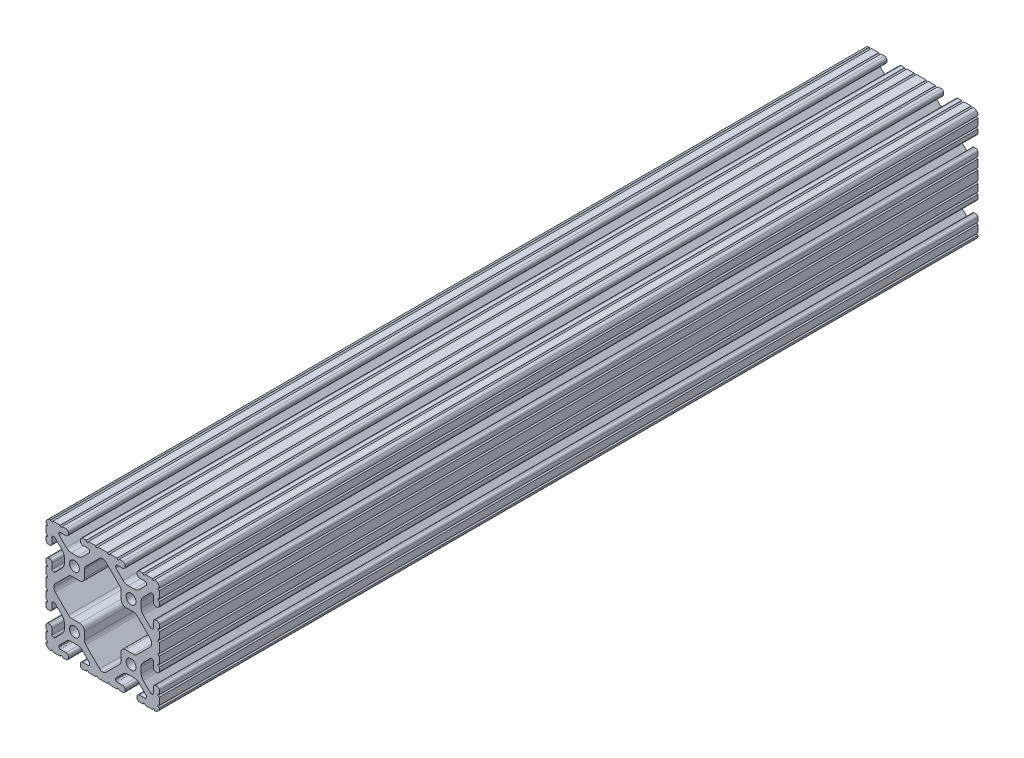
SolidWorks part; units mm, degrees
ref_plane "Front Plane" through (0, 0, 0) normal (0, 0, 1) x (1, 0, 0)
ref_plane "Top Plane" through (0, 0, 0) normal (0, 1, 0) x (1, 0, 0)
ref_plane "Right Plane" through (0, 0, 0) normal (1, 0, 0) x (0, 0, -1)
sketch "Sketch1" plane through (0, 0, 0) normal (0, 0, 1) x (1, 0, 0)
  line L0 (0, 38.1) -> (0, -38.1) construction
  line L1 (-38.1, -38.1) -> (38.1, -38.1) construction
  line L2 (-38.1, -38.1) -> (-38.1, 38.1) construction
  line L3 (-38.1, 38.1) -> (38.1, 38.1) construction
  line L4 (38.1, -38.1) -> (38.1, 38.1) construction
  line L5 (0, 38.1) -> (0, -38.1) construction
  line L6 (-38.1, 0) -> (38.1, 0) construction
  line L7 (-19.05, 19.05) -> (19.05, 19.05) construction
  line L8 (-19.05, 19.05) -> (-19.05, -19.05) construction
  line L9 (-19.05, -19.05) -> (19.05, -19.05) construction
  line L10 (19.05, 19.05) -> (19.05, -19.05) construction
  line L11 (-23.114, 38.1) -> (-23.114, -38.1) construction
  line L12 (-23.114, -38.1) -> (-14.986, 38.1) construction
  line L13 (-14.986, 38.1) -> (-14.986, -38.1) construction
  circle A0 centre (19.05, 19.05) radius 3.3274
  point P0 (0, 0)
  point P9 (0, 0)
  point P12 (-19.05, 0)
  line B0 (-11.3637, -22.8433) -> (-2.0515, -32.1555)
  line B1 (-12.2936, -15.4686) -> (-12.2936, -20.5983)
  line B2 (-20.769, -12.2936) -> (-15.4686, -12.2936)
  line B3 (-31.9021, -2.4756) -> (-23.0141, -11.3637)
  line B4 (-23.0141, 11.3637) -> (-31.9021, 2.4756)
  line B5 (-15.4686, 12.2936) -> (-20.769, 12.2936)
  line B6 (-12.2936, 20.5983) -> (-12.2936, 15.4686)
  line B7 (-2.0515, 32.1555) -> (-11.3637, 22.8433)
  line B8 (11.3637, 22.8433) -> (2.0515, 32.1555)
  line B9 (12.2936, 15.4686) -> (12.2936, 20.5983)
  line B10 (20.769, 12.2936) -> (15.4686, 12.2936)
  line B11 (31.9021, 2.4756) -> (23.0141, 11.3637)
  line B12 (23.0141, -11.3637) -> (31.9021, -2.4756)
  line B13 (15.4686, -12.2936) -> (20.769, -12.2936)
  line B14 (12.2936, -20.5983) -> (12.2936, -15.4686)
  line B15 (2.0515, -32.1555) -> (11.3637, -22.8433)
  line B16 (-4.7773, 38.1) -> (-9.6053, 38.1)
  line B17 (-11.1289, 38.1) -> (-13.4112, 38.1)
  line B18 (-14.986, 36.5252) -> (-14.986, 35.6108)
  line B19 (-13.4112, 34.036) -> (-9.652, 34.036)
  line B20 (-8.763, 33.147) -> (-8.763, 32.4935)
  line B21 (-9.0234, 31.8649) -> (-13.6907, 27.1976)
  line B22 (-17.0493, 25.8064) -> (-21.0507, 25.8064)
  line B23 (-24.4093, 27.1976) -> (-29.1002, 31.8885)
  line B24 (-29.337, 32.7207) -> (-29.337, 33.147)
  line B25 (-28.448, 34.036) -> (-24.6888, 34.036)
  line B26 (-23.114, 35.6108) -> (-23.114, 36.5252)
  line B27 (-24.6888, 38.1) -> (-27.0772, 38.1)
  line B28 (-28.6011, 38.1) -> (-33.4288, 38.1)
  line B29 (-38.1, 33.373) -> (-38.1, 28.5453)
  line B30 (-38.1, 27.0238) -> (-38.1, 24.6302)
  line B31 (-36.5252, 23.0554) -> (-35.6108, 23.0554)
  line B32 (-34.036, 24.6302) -> (-34.036, 28.448)
  line B33 (-33.147, 29.337) -> (-32.6643, 29.337)
  line B34 (-32.0357, 29.0766) -> (-27.1976, 24.2385)
  line B35 (-25.8064, 20.8799) -> (-25.8064, 17.2201)
  line B36 (-27.1976, 13.8615) -> (-31.9489, 9.1101)
  line B37 (-32.7869, 8.763) -> (-33.0603, 8.763)
  line B38 (-34.036, 9.7387) -> (-34.036, 13.4698)
  line B39 (-35.6108, 15.0446) -> (-36.5252, 15.0446)
  line B40 (-38.1, 13.4698) -> (-38.1, 11.075)
  line B41 (-38.1, 9.552) -> (-38.1, 4.7238)
  line B42 (-38.1, 3.2007) -> (-38.1, -3.2007)
  line B43 (-38.1, -4.7238) -> (-38.1, -9.552)
  line B44 (-38.1, -11.075) -> (-38.1, -13.4698)
  line B45 (-36.5252, -15.0446) -> (-35.6108, -15.0446)
  line B46 (-34.036, -13.4698) -> (-34.036, -9.7387)
  line B47 (-33.0603, -8.763) -> (-32.7869, -8.763)
  line B48 (-31.9489, -9.1101) -> (-27.1976, -13.8615)
  line B49 (-25.8064, -17.2201) -> (-25.8064, -20.8799)
  line B50 (-27.1976, -24.2385) -> (-32.0357, -29.0766)
  line B51 (-32.6643, -29.337) -> (-33.147, -29.337)
  line B52 (-34.036, -28.448) -> (-34.036, -24.6302)
  line B53 (-35.6108, -23.0554) -> (-36.5252, -23.0554)
  line B54 (-38.1, -24.6302) -> (-38.1, -27.0238)
  line B55 (-38.1, -28.5453) -> (-38.1, -33.373)
  line B56 (-33.4288, -38.1) -> (-28.6011, -38.1)
  line B57 (-27.0772, -38.1) -> (-24.6888, -38.1)
  line B58 (-23.114, -36.5252) -> (-23.114, -35.6108)
  line B59 (-24.6888, -34.036) -> (-28.448, -34.036)
  line B60 (-29.337, -33.147) -> (-29.337, -32.7207)
  line B61 (-29.1002, -31.8885) -> (-24.4093, -27.1976)
  line B62 (-21.0507, -25.8064) -> (-17.0493, -25.8064)
  line B63 (-13.6907, -27.1976) -> (-9.0234, -31.8649)
  line B64 (-8.763, -32.4935) -> (-8.763, -33.147)
  line B65 (-9.652, -34.036) -> (-13.4112, -34.036)
  line B66 (-14.986, -35.6108) -> (-14.986, -36.5252)
  line B67 (-13.4112, -38.1) -> (-11.1289, -38.1)
  line B68 (-9.6053, -38.1) -> (-4.7773, -38.1)
  line B69 (-3.2537, -38.1) -> (3.2537, -38.1)
  line B70 (4.7773, -38.1) -> (9.6053, -38.1)
  line B71 (11.1289, -38.1) -> (13.4112, -38.1)
  line B72 (14.986, -36.5252) -> (14.986, -35.6108)
  line B73 (13.4112, -34.036) -> (9.652, -34.036)
  line B74 (8.763, -33.147) -> (8.763, -32.4935)
  line B75 (9.0234, -31.8649) -> (13.6907, -27.1976)
  line B76 (17.0493, -25.8064) -> (21.0507, -25.8064)
  line B77 (24.4093, -27.1976) -> (29.1002, -31.8885)
  line B78 (29.337, -32.7207) -> (29.337, -33.147)
  line B79 (28.448, -34.036) -> (24.6888, -34.036)
  line B80 (23.114, -35.6108) -> (23.114, -36.5252)
  line B81 (24.6888, -38.1) -> (27.0772, -38.1)
  line B82 (28.6011, -38.1) -> (33.4288, -38.1)
  line B83 (38.1, -33.373) -> (38.1, -28.5453)
  line B84 (38.1, -27.0238) -> (38.1, -24.6302)
  line B85 (36.5252, -23.0554) -> (35.6108, -23.0554)
  line B86 (34.036, -24.6302) -> (34.036, -28.448)
  line B87 (33.147, -29.337) -> (32.6643, -29.337)
  line B88 (32.0357, -29.0766) -> (27.1976, -24.2385)
  line B89 (25.8064, -20.8799) -> (25.8064, -17.2201)
  line B90 (27.1976, -13.8615) -> (31.9489, -9.1101)
  line B91 (32.7869, -8.763) -> (33.0603, -8.763)
  line B92 (34.036, -9.7387) -> (34.036, -13.4698)
  line B93 (35.6108, -15.0446) -> (36.5252, -15.0446)
  line B94 (38.1, -13.4698) -> (38.1, -11.075)
  line B95 (38.1, -9.552) -> (38.1, -4.7238)
  line B96 (38.1, -3.2007) -> (38.1, 3.2007)
  line B97 (38.1, 4.7238) -> (38.1, 9.552)
  line B98 (38.1, 11.075) -> (38.1, 13.4698)
  line B99 (36.5252, 15.0446) -> (35.6108, 15.0446)
  line B100 (34.036, 13.4698) -> (34.036, 9.7387)
  line B101 (33.0603, 8.763) -> (32.7869, 8.763)
  line B102 (31.9489, 9.1101) -> (27.1976, 13.8615)
  line B103 (25.8064, 17.2201) -> (25.8064, 20.8799)
  line B104 (27.1976, 24.2385) -> (32.0357, 29.0766)
  line B105 (32.6643, 29.337) -> (33.147, 29.337)
  line B106 (34.036, 28.448) -> (34.036, 24.6302)
  line B107 (35.6108, 23.0554) -> (36.5252, 23.0554)
  line B108 (38.1, 24.6302) -> (38.1, 27.0238)
  line B109 (38.1, 28.5453) -> (38.1, 33.373)
  line B110 (33.4288, 38.1) -> (28.6011, 38.1)
  line B111 (27.0772, 38.1) -> (24.6888, 38.1)
  line B112 (23.114, 36.5252) -> (23.114, 35.6108)
  line B113 (24.6888, 34.036) -> (28.448, 34.036)
  line B114 (29.337, 33.147) -> (29.337, 32.7207)
  line B115 (29.1002, 31.8885) -> (24.4093, 27.1976)
  line B116 (21.0507, 25.8064) -> (17.0493, 25.8064)
  line B117 (13.6907, 27.1976) -> (9.0234, 31.8649)
  line B118 (8.763, 32.4935) -> (8.763, 33.147)
  line B119 (9.652, 34.036) -> (13.4112, 34.036)
  line B120 (14.986, 35.6108) -> (14.986, 36.5252)
  line B121 (13.4112, 38.1) -> (11.1289, 38.1)
  line B122 (9.6053, 38.1) -> (4.7773, 38.1)
  line B123 (3.2537, 38.1) -> (-3.2537, 38.1)
  circle B124 centre (-19.05, 19.05) radius 3.3274
  circle B125 centre (-19.05, -19.05) radius 3.3274
  circle B126 centre (19.05, -19.05) radius 3.3274
  circle B127 centre (19.05, 19.05) radius 3.3274
  arc B128 (0, -33.011) -> (2.0515, -32.1555) centre (-0.0139, -30.09) ccw
  arc B129 (-2.0515, -32.1555) -> (0, -33.011) centre (0.0139, -30.09) ccw
  arc B130 (-12.2936, -20.5983) -> (-11.3637, -22.8433) centre (-9.1186, -20.5983) ccw
  arc B131 (-12.2936, -15.4686) -> (-15.4686, -12.2936) centre (-15.4686, -15.4686) ccw
  arc B132 (-23.0141, -11.3637) -> (-20.769, -12.2936) centre (-20.769, -9.1186) ccw
  arc B133 (-32.7287, 0) -> (-31.9021, -2.4756) centre (-29.8367, -0.4102) ccw
  arc B134 (-31.9021, 2.4756) -> (-32.7287, 0) centre (-29.8367, 0.4102) ccw
  arc B135 (-20.769, 12.2936) -> (-23.0141, 11.3637) centre (-20.769, 9.1186) ccw
  arc B136 (-15.4686, 12.2936) -> (-12.2936, 15.4686) centre (-15.4686, 15.4686) ccw
  arc B137 (-11.3637, 22.8433) -> (-12.2936, 20.5983) centre (-9.1186, 20.5983) ccw
  arc B138 (0, 33.011) -> (-2.0515, 32.1555) centre (0.0139, 30.09) ccw
  arc B139 (2.0515, 32.1555) -> (0, 33.011) centre (-0.0139, 30.09) ccw
  arc B140 (12.2936, 20.5983) -> (11.3637, 22.8433) centre (9.1186, 20.5983) ccw
  arc B141 (12.2936, 15.4686) -> (15.4686, 12.2936) centre (15.4686, 15.4686) ccw
  arc B142 (23.0141, 11.3637) -> (20.769, 12.2936) centre (20.769, 9.1186) ccw
  arc B143 (32.7287, 0) -> (31.9021, 2.4756) centre (29.8367, 0.4102) ccw
  arc B144 (31.9021, -2.4756) -> (32.7287, 0) centre (29.8367, -0.4102) ccw
  arc B145 (20.769, -12.2936) -> (23.0141, -11.3637) centre (20.769, -9.1186) ccw
  arc B146 (15.4686, -12.2936) -> (12.2936, -15.4686) centre (15.4686, -15.4686) ccw
  arc B147 (11.3637, -22.8433) -> (12.2936, -20.5983) centre (9.1186, -20.5983) ccw
  arc B148 (-4.7773, 38.1) -> (-3.2537, 38.1) centre (-4.0155, 38.0824) ccw
  arc B149 (-11.1289, 38.1) -> (-9.6053, 38.1) centre (-10.3671, 38.0824) ccw
  arc B150 (-13.4112, 38.1) -> (-14.986, 36.5252) centre (-13.4112, 36.5252) ccw
  arc B151 (-14.986, 35.6108) -> (-13.4112, 34.036) centre (-13.4112, 35.6108) ccw
  arc B152 (-8.763, 33.147) -> (-9.652, 34.036) centre (-9.652, 33.147) ccw
  arc B153 (-9.0234, 31.8649) -> (-8.763, 32.4935) centre (-9.652, 32.4935) ccw
  arc B154 (-17.0493, 25.8064) -> (-13.6907, 27.1976) centre (-17.0493, 30.5562) ccw
  arc B155 (-24.4093, 27.1976) -> (-21.0507, 25.8064) centre (-21.0507, 30.5562) ccw
  arc B156 (-29.337, 32.7207) -> (-29.1002, 31.8885) centre (-28.4716, 32.5172) ccw
  arc B157 (-28.448, 34.036) -> (-29.337, 33.147) centre (-28.448, 33.147) ccw
  arc B158 (-24.6888, 34.036) -> (-23.114, 35.6108) centre (-24.6888, 35.6108) ccw
  arc B159 (-23.114, 36.5252) -> (-24.6888, 38.1) centre (-24.6888, 36.5252) ccw
  arc B160 (-28.6011, 38.1) -> (-27.0772, 38.1) centre (-27.8392, 38.0824) ccw
  arc B161 (-34.9527, 38.1) -> (-33.4288, 38.1) centre (-34.1907, 38.0824) ccw
  arc B162 (-34.9527, 38.1) -> (-37.0861, 37.1826) centre (-34.8521, 34.9266) ccw
  arc B163 (-37.0861, 37.1826) -> (-38.1, 34.8455) centre (-34.925, 34.8566) ccw
  arc B164 (-38.1, 33.373) -> (-38.1, 34.8455) centre (-37.9035, 34.1092) ccw
  arc B165 (-38.1, 27.0238) -> (-38.1, 28.5453) centre (-37.9035, 27.7845) ccw
  arc B166 (-38.1, 24.6302) -> (-36.5252, 23.0554) centre (-36.5252, 24.6302) ccw
  arc B167 (-35.6108, 23.0554) -> (-34.036, 24.6302) centre (-35.6108, 24.6302) ccw
  arc B168 (-33.147, 29.337) -> (-34.036, 28.448) centre (-33.147, 28.448) ccw
  arc B169 (-32.0357, 29.0766) -> (-32.6643, 29.337) centre (-32.6643, 28.448) ccw
  arc B170 (-25.8064, 20.8799) -> (-27.1976, 24.2385) centre (-30.5562, 20.8799) ccw
  arc B171 (-27.1976, 13.8615) -> (-25.8064, 17.2201) centre (-30.5562, 17.2201) ccw
  arc B172 (-32.7869, 8.763) -> (-31.9489, 9.1101) centre (-32.7869, 9.9481) ccw
  arc B173 (-34.036, 9.7387) -> (-33.0603, 8.763) centre (-33.0603, 9.7387) ccw
  arc B174 (-34.036, 13.4698) -> (-35.6108, 15.0446) centre (-35.6108, 13.4698) ccw
  arc B175 (-36.5252, 15.0446) -> (-38.1, 13.4698) centre (-36.5252, 13.4698) ccw
  arc B176 (-38.1, 9.552) -> (-38.1, 11.075) centre (-37.9035, 10.3135) ccw
  arc B177 (-38.1, 3.2007) -> (-38.1, 4.7238) centre (-37.9035, 3.9622) ccw
  arc B178 (-38.1, -4.7238) -> (-38.1, -3.2007) centre (-37.9035, -3.9622) ccw
  arc B179 (-38.1, -11.075) -> (-38.1, -9.552) centre (-37.9035, -10.3135) ccw
  arc B180 (-38.1, -13.4698) -> (-36.5252, -15.0446) centre (-36.5252, -13.4698) ccw
  arc B181 (-35.6108, -15.0446) -> (-34.036, -13.4698) centre (-35.6108, -13.4698) ccw
  arc B182 (-33.0603, -8.763) -> (-34.036, -9.7387) centre (-33.0603, -9.7387) ccw
  arc B183 (-31.9489, -9.1101) -> (-32.7869, -8.763) centre (-32.7869, -9.9481) ccw
  arc B184 (-25.8064, -17.2201) -> (-27.1976, -13.8615) centre (-30.5562, -17.2201) ccw
  arc B185 (-27.1976, -24.2385) -> (-25.8064, -20.8799) centre (-30.5562, -20.8799) ccw
  arc B186 (-32.6643, -29.337) -> (-32.0357, -29.0766) centre (-32.6643, -28.448) ccw
  arc B187 (-34.036, -28.448) -> (-33.147, -29.337) centre (-33.147, -28.448) ccw
  arc B188 (-34.036, -24.6302) -> (-35.6108, -23.0554) centre (-35.6108, -24.6302) ccw
  arc B189 (-36.5252, -23.0554) -> (-38.1, -24.6302) centre (-36.5252, -24.6302) ccw
  arc B190 (-38.1, -28.5453) -> (-38.1, -27.0238) centre (-37.9035, -27.7845) ccw
  arc B191 (-38.1, -34.8455) -> (-38.1, -33.373) centre (-37.9035, -34.1092) ccw
  arc B192 (-38.1, -34.8455) -> (-37.0861, -37.1826) centre (-34.925, -34.8566) ccw
  arc B193 (-37.0861, -37.1826) -> (-34.9527, -38.1) centre (-34.8521, -34.9266) ccw
  arc B194 (-33.4288, -38.1) -> (-34.9527, -38.1) centre (-34.1907, -38.0824) ccw
  arc B195 (-27.0772, -38.1) -> (-28.6011, -38.1) centre (-27.8392, -38.0824) ccw
  arc B196 (-24.6888, -38.1) -> (-23.114, -36.5252) centre (-24.6888, -36.5252) ccw
  arc B197 (-23.114, -35.6108) -> (-24.6888, -34.036) centre (-24.6888, -35.6108) ccw
  arc B198 (-29.337, -33.147) -> (-28.448, -34.036) centre (-28.448, -33.147) ccw
  arc B199 (-29.1002, -31.8885) -> (-29.337, -32.7207) centre (-28.4716, -32.5172) ccw
  arc B200 (-21.0507, -25.8064) -> (-24.4093, -27.1976) centre (-21.0507, -30.5562) ccw
  arc B201 (-13.6907, -27.1976) -> (-17.0493, -25.8064) centre (-17.0493, -30.5562) ccw
  arc B202 (-8.763, -32.4935) -> (-9.0234, -31.8649) centre (-9.652, -32.4935) ccw
  arc B203 (-9.652, -34.036) -> (-8.763, -33.147) centre (-9.652, -33.147) ccw
  arc B204 (-13.4112, -34.036) -> (-14.986, -35.6108) centre (-13.4112, -35.6108) ccw
  arc B205 (-14.986, -36.5252) -> (-13.4112, -38.1) centre (-13.4112, -36.5252) ccw
  arc B206 (-9.6053, -38.1) -> (-11.1289, -38.1) centre (-10.3671, -38.0824) ccw
  arc B207 (-3.2537, -38.1) -> (-4.7773, -38.1) centre (-4.0155, -38.0824) ccw
  arc B208 (4.7773, -38.1) -> (3.2537, -38.1) centre (4.0155, -38.0824) ccw
  arc B209 (11.1289, -38.1) -> (9.6053, -38.1) centre (10.3671, -38.0824) ccw
  arc B210 (13.4112, -38.1) -> (14.986, -36.5252) centre (13.4112, -36.5252) ccw
  arc B211 (14.986, -35.6108) -> (13.4112, -34.036) centre (13.4112, -35.6108) ccw
  arc B212 (8.763, -33.147) -> (9.652, -34.036) centre (9.652, -33.147) ccw
  arc B213 (9.0234, -31.8649) -> (8.763, -32.4935) centre (9.652, -32.4935) ccw
  arc B214 (17.0493, -25.8064) -> (13.6907, -27.1976) centre (17.0493, -30.5562) ccw
  arc B215 (24.4093, -27.1976) -> (21.0507, -25.8064) centre (21.0507, -30.5562) ccw
  arc B216 (29.337, -32.7207) -> (29.1002, -31.8885) centre (28.4716, -32.5172) ccw
  arc B217 (28.448, -34.036) -> (29.337, -33.147) centre (28.448, -33.147) ccw
  arc B218 (24.6888, -34.036) -> (23.114, -35.6108) centre (24.6888, -35.6108) ccw
  arc B219 (23.114, -36.5252) -> (24.6888, -38.1) centre (24.6888, -36.5252) ccw
  arc B220 (28.6011, -38.1) -> (27.0772, -38.1) centre (27.8392, -38.0824) ccw
  arc B221 (34.9527, -38.1) -> (33.4288, -38.1) centre (34.1907, -38.0824) ccw
  arc B222 (34.9527, -38.1) -> (37.0861, -37.1826) centre (34.8521, -34.9266) ccw
  arc B223 (37.0861, -37.1826) -> (38.1, -34.8455) centre (34.925, -34.8566) ccw
  arc B224 (38.1, -33.373) -> (38.1, -34.8455) centre (37.9035, -34.1092) ccw
  arc B225 (38.1, -27.0238) -> (38.1, -28.5453) centre (37.9035, -27.7845) ccw
  arc B226 (38.1, -24.6302) -> (36.5252, -23.0554) centre (36.5252, -24.6302) ccw
  arc B227 (35.6108, -23.0554) -> (34.036, -24.6302) centre (35.6108, -24.6302) ccw
  arc B228 (33.147, -29.337) -> (34.036, -28.448) centre (33.147, -28.448) ccw
  arc B229 (32.0357, -29.0766) -> (32.6643, -29.337) centre (32.6643, -28.448) ccw
  arc B230 (25.8064, -20.8799) -> (27.1976, -24.2385) centre (30.5562, -20.8799) ccw
  arc B231 (27.1976, -13.8615) -> (25.8064, -17.2201) centre (30.5562, -17.2201) ccw
  arc B232 (32.7869, -8.763) -> (31.9489, -9.1101) centre (32.7869, -9.9481) ccw
  arc B233 (34.036, -9.7387) -> (33.0603, -8.763) centre (33.0603, -9.7387) ccw
  arc B234 (34.036, -13.4698) -> (35.6108, -15.0446) centre (35.6108, -13.4698) ccw
  arc B235 (36.5252, -15.0446) -> (38.1, -13.4698) centre (36.5252, -13.4698) ccw
  arc B236 (38.1, -9.552) -> (38.1, -11.075) centre (37.9035, -10.3135) ccw
  arc B237 (38.1, -3.2007) -> (38.1, -4.7238) centre (37.9035, -3.9622) ccw
  arc B238 (38.1, 4.7238) -> (38.1, 3.2007) centre (37.9035, 3.9622) ccw
  arc B239 (38.1, 11.075) -> (38.1, 9.552) centre (37.9035, 10.3135) ccw
  arc B240 (38.1, 13.4698) -> (36.5252, 15.0446) centre (36.5252, 13.4698) ccw
  arc B241 (35.6108, 15.0446) -> (34.036, 13.4698) centre (35.6108, 13.4698) ccw
  arc B242 (33.0603, 8.763) -> (34.036, 9.7387) centre (33.0603, 9.7387) ccw
  arc B243 (31.9489, 9.1101) -> (32.7869, 8.763) centre (32.7869, 9.9481) ccw
  arc B244 (25.8064, 17.2201) -> (27.1976, 13.8615) centre (30.5562, 17.2201) ccw
  arc B245 (27.1976, 24.2385) -> (25.8064, 20.8799) centre (30.5562, 20.8799) ccw
  arc B246 (32.6643, 29.337) -> (32.0357, 29.0766) centre (32.6643, 28.448) ccw
  arc B247 (34.036, 28.448) -> (33.147, 29.337) centre (33.147, 28.448) ccw
  arc B248 (34.036, 24.6302) -> (35.6108, 23.0554) centre (35.6108, 24.6302) ccw
  arc B249 (36.5252, 23.0554) -> (38.1, 24.6302) centre (36.5252, 24.6302) ccw
  arc B250 (38.1, 28.5453) -> (38.1, 27.0238) centre (37.9035, 27.7845) ccw
  arc B251 (38.1, 34.8455) -> (38.1, 33.373) centre (37.9035, 34.1092) ccw
  arc B252 (38.1, 34.8455) -> (37.0861, 37.1826) centre (34.925, 34.8566) ccw
  arc B253 (37.0861, 37.1826) -> (34.9527, 38.1) centre (34.8521, 34.9266) ccw
  arc B254 (33.4288, 38.1) -> (34.9527, 38.1) centre (34.1907, 38.0824) ccw
  arc B255 (27.0772, 38.1) -> (28.6011, 38.1) centre (27.8392, 38.0824) ccw
  arc B256 (24.6888, 38.1) -> (23.114, 36.5252) centre (24.6888, 36.5252) ccw
  arc B257 (23.114, 35.6108) -> (24.6888, 34.036) centre (24.6888, 35.6108) ccw
  arc B258 (29.337, 33.147) -> (28.448, 34.036) centre (28.448, 33.147) ccw
  arc B259 (29.1002, 31.8885) -> (29.337, 32.7207) centre (28.4716, 32.5172) ccw
  arc B260 (21.0507, 25.8064) -> (24.4093, 27.1976) centre (21.0507, 30.5562) ccw
  arc B261 (13.6907, 27.1976) -> (17.0493, 25.8064) centre (17.0493, 30.5562) ccw
  arc B262 (8.763, 32.4935) -> (9.0234, 31.8649) centre (9.652, 32.4935) ccw
  arc B263 (9.652, 34.036) -> (8.763, 33.147) centre (9.652, 33.147) ccw
  arc B264 (13.4112, 34.036) -> (14.986, 35.6108) centre (13.4112, 35.6108) ccw
  arc B265 (14.986, 36.5252) -> (13.4112, 38.1) centre (13.4112, 36.5252) ccw
  arc B266 (9.6053, 38.1) -> (11.1289, 38.1) centre (10.3671, 38.0824) ccw
  arc B267 (3.2537, 38.1) -> (4.7773, 38.1) centre (4.0155, 38.0824) ccw
  dimension "Center Hole Diameter" = 6.6548
  dimension "Rail Width" = 76.2
  dimension "Rail Height" = 76.2
  dimension "T-Slot Width" = 8.128
sketch_block_instance "Block1-1"
sketch_block "Block1"
sketch "Sketch2" plane through (0, 0, 0) normal (1, 0, 0) x (0, 0, -1)
  line L0 (-275, 0) -> (275, 0) construction
  line L1 (-275, 38.1) -> (-275, -38.1) construction
  line L2 (-275, -38.1) -> (275, -38.1) construction
  line L3 (275, -38.1) -> (275, 38.1) construction
  line L4 (-173.4, 0) -> (-173.4, 38.1) construction
  line L5 (-173.4, 38.1) -> (173.4, 38.1) construction
  line L6 (173.4, 38.1) -> (173.4, 0) construction
  point P5 (173.4, 0)
  point P10 (-173.4, 0)
  dimension "D1" = 101.6
  dimension "Length" = 550
  dimension "D2" = 101.6
sketch "Sketch3" plane through (0, 0, 0) normal (0, 0, 1) x (1, 0, 0)
  line L0 (-11.3637, -22.8433) -> (-2.0515, -32.1555) construction
  line L1 (-12.2936, -15.4686) -> (-12.2936, -20.5983) construction
  line L2 (-20.769, -12.2936) -> (-15.4686, -12.2936) construction
  line L3 (-31.9021, -2.4756) -> (-23.0141, -11.3637) construction
  line L4 (-23.0141, 11.3637) -> (-31.9021, 2.4756) construction
  line L5 (-15.4686, 12.2936) -> (-20.769, 12.2936) construction
  line L6 (-12.2936, 20.5983) -> (-12.2936, 15.4686) construction
  line L7 (-2.0515, 32.1555) -> (-11.3637, 22.8433) construction
  line L8 (11.3637, 22.8433) -> (2.0515, 32.1555) construction
  line L9 (12.2936, 15.4686) -> (12.2936, 20.5983) construction
  line L10 (20.769, 12.2936) -> (15.4686, 12.2936) construction
  line L11 (31.9021, 2.4756) -> (23.0141, 11.3637) construction
  line L12 (23.0141, -11.3637) -> (31.9021, -2.4756) construction
  line L13 (15.4686, -12.2936) -> (20.769, -12.2936) construction
  line L14 (12.2936, -20.5983) -> (12.2936, -15.4686) construction
  line L15 (2.0515, -32.1555) -> (11.3637, -22.8433) construction
  line L16 (34.036, 28.448) -> (34.036, 24.6302) construction
  line L17 (35.6108, 23.0554) -> (36.5252, 23.0554) construction
  line L18 (38.1, 24.6302) -> (38.1, 27.0238) construction
  line L19 (38.1, 28.5453) -> (38.1, 33.373) construction
  line L20 (33.4288, 38.1) -> (28.6011, 38.1) construction
  line L21 (27.0772, 38.1) -> (24.6888, 38.1) construction
  line L22 (23.114, 36.5252) -> (23.114, 35.6108) construction
  line L23 (24.6888, 34.036) -> (28.448, 34.036) construction
  line L24 (29.337, 33.147) -> (29.337, 32.7207) construction
  line L25 (29.1002, 31.8885) -> (24.4093, 27.1976) construction
  line L26 (21.0507, 25.8064) -> (17.0493, 25.8064) construction
  line L27 (13.6907, 27.1976) -> (9.0234, 31.8649) construction
  line L28 (8.763, 32.4935) -> (8.763, 33.147) construction
  line L29 (9.652, 34.036) -> (13.4112, 34.036) construction
  line L30 (14.986, 35.6108) -> (14.986, 36.5252) construction
  line L31 (13.4112, 38.1) -> (11.1289, 38.1) construction
  line L32 (9.6053, 38.1) -> (4.7773, 38.1) construction
  line L33 (3.2537, 38.1) -> (-3.2537, 38.1) construction
  line L34 (-4.7773, 38.1) -> (-9.6053, 38.1) construction
  line L35 (-11.1289, 38.1) -> (-13.4112, 38.1) construction
  line L36 (-14.986, 36.5252) -> (-14.986, 35.6108) construction
  line L37 (-13.4112, 34.036) -> (-9.652, 34.036) construction
  line L38 (-8.763, 33.147) -> (-8.763, 32.4935) construction
  line L39 (-9.0234, 31.8649) -> (-13.6907, 27.1976) construction
  line L40 (-17.0493, 25.8064) -> (-21.0507, 25.8064) construction
  line L41 (-24.4093, 27.1976) -> (-29.1002, 31.8885) construction
  line L42 (-29.337, 32.7207) -> (-29.337, 33.147) construction
  line L43 (-28.448, 34.036) -> (-24.6888, 34.036) construction
  line L44 (-23.114, 35.6108) -> (-23.114, 36.5252) construction
  line L45 (-24.6888, 38.1) -> (-27.0772, 38.1) construction
  line L46 (-28.6011, 38.1) -> (-33.4288, 38.1) construction
  line L47 (-38.1, 33.373) -> (-38.1, 28.5453) construction
  line L48 (-38.1, 27.0238) -> (-38.1, 24.6302) construction
  line L49 (-36.5252, 23.0554) -> (-35.6108, 23.0554) construction
  line L50 (-34.036, 24.6302) -> (-34.036, 28.448) construction
  line L51 (-33.147, 29.337) -> (-32.6643, 29.337) construction
  line L52 (-32.0357, 29.0766) -> (-27.1976, 24.2385) construction
  line L53 (-25.8064, 20.8799) -> (-25.8064, 17.2201) construction
  line L54 (-27.1976, 13.8615) -> (-31.9489, 9.1101) construction
  line L55 (-32.7869, 8.763) -> (-33.0603, 8.763) construction
  line L56 (-34.036, 9.7387) -> (-34.036, 13.4698) construction
  line L57 (-35.6108, 15.0446) -> (-36.5252, 15.0446) construction
  line L58 (-38.1, 13.4698) -> (-38.1, 11.075) construction
  line L59 (-38.1, 9.552) -> (-38.1, 4.7238) construction
  line L60 (-38.1, 3.2007) -> (-38.1, -3.2007) construction
  line L61 (-38.1, -4.7238) -> (-38.1, -9.552) construction
  line L62 (-38.1, -11.075) -> (-38.1, -13.4698) construction
  line L63 (-36.5252, -15.0446) -> (-35.6108, -15.0446) construction
  line L64 (-34.036, -13.4698) -> (-34.036, -9.7387) construction
  line L65 (-33.0603, -8.763) -> (-32.7869, -8.763) construction
  line L66 (-31.9489, -9.1101) -> (-27.1976, -13.8615) construction
  line L67 (-25.8064, -17.2201) -> (-25.8064, -20.8799) construction
  line L68 (-27.1976, -24.2385) -> (-32.0357, -29.0766) construction
  line L69 (-32.6643, -29.337) -> (-33.147, -29.337) construction
  line L70 (-34.036, -28.448) -> (-34.036, -24.6302) construction
  line L71 (-35.6108, -23.0554) -> (-36.5252, -23.0554) construction
  line L72 (-38.1, -24.6302) -> (-38.1, -27.0238) construction
  line L73 (-38.1, -28.5453) -> (-38.1, -33.373) construction
  line L74 (-33.4288, -38.1) -> (-28.6011, -38.1) construction
  line L75 (-27.0772, -38.1) -> (-24.6888, -38.1) construction
  line L76 (-23.114, -36.5252) -> (-23.114, -35.6108) construction
  line L77 (-24.6888, -34.036) -> (-28.448, -34.036) construction
  line L78 (-29.337, -33.147) -> (-29.337, -32.7207) construction
  line L79 (-29.1002, -31.8885) -> (-24.4093, -27.1976) construction
  line L80 (-21.0507, -25.8064) -> (-17.0493, -25.8064) construction
  line L81 (-13.6907, -27.1976) -> (-9.0234, -31.8649) construction
  line L82 (-8.763, -32.4935) -> (-8.763, -33.147) construction
  line L83 (-9.652, -34.036) -> (-13.4112, -34.036) construction
  line L84 (-14.986, -35.6108) -> (-14.986, -36.5252) construction
  line L85 (-13.4112, -38.1) -> (-11.1289, -38.1) construction
  line L86 (-9.6053, -38.1) -> (-4.7773, -38.1) construction
  line L87 (-3.2537, -38.1) -> (3.2537, -38.1) construction
  line L88 (4.7773, -38.1) -> (9.6053, -38.1) construction
  line L89 (11.1289, -38.1) -> (13.4112, -38.1) construction
  line L90 (14.986, -36.5252) -> (14.986, -35.6108) construction
  line L91 (13.4112, -34.036) -> (9.652, -34.036) construction
  line L92 (8.763, -33.147) -> (8.763, -32.4935) construction
  line L93 (9.0234, -31.8649) -> (13.6907, -27.1976) construction
  line L94 (17.0493, -25.8064) -> (21.0507, -25.8064) construction
  line L95 (24.4093, -27.1976) -> (29.1002, -31.8885) construction
  line L96 (29.337, -32.7207) -> (29.337, -33.147) construction
  line L97 (28.448, -34.036) -> (24.6888, -34.036) construction
  line L98 (23.114, -35.6108) -> (23.114, -36.5252) construction
  line L99 (24.6888, -38.1) -> (27.0772, -38.1) construction
  line L100 (28.6011, -38.1) -> (33.4288, -38.1) construction
  line L101 (38.1, -33.373) -> (38.1, -28.5453) construction
  line L102 (38.1, -27.0238) -> (38.1, -24.6302) construction
  line L103 (36.5252, -23.0554) -> (35.6108, -23.0554) construction
  line L104 (34.036, -24.6302) -> (34.036, -28.448) construction
  line L105 (33.147, -29.337) -> (32.6643, -29.337) construction
  line L106 (32.0357, -29.0766) -> (27.1976, -24.2385) construction
  line L107 (25.8064, -20.8799) -> (25.8064, -17.2201) construction
  line L108 (27.1976, -13.8615) -> (31.9489, -9.1101) construction
  line L109 (32.7869, -8.763) -> (33.0603, -8.763) construction
  line L110 (34.036, -9.7387) -> (34.036, -13.4698) construction
  line L111 (35.6108, -15.0446) -> (36.5252, -15.0446) construction
  line L112 (38.1, -13.4698) -> (38.1, -11.075) construction
  line L113 (38.1, -9.552) -> (38.1, -4.7238) construction
  line L114 (38.1, -3.2007) -> (38.1, 3.2007) construction
  line L115 (38.1, 4.7238) -> (38.1, 9.552) construction
  line L116 (38.1, 11.075) -> (38.1, 13.4698) construction
  line L117 (36.5252, 15.0446) -> (35.6108, 15.0446) construction
  line L118 (34.036, 13.4698) -> (34.036, 9.7387) construction
  line L119 (33.0603, 8.763) -> (32.7869, 8.763) construction
  line L120 (31.9489, 9.1101) -> (27.1976, 13.8615) construction
  line L121 (25.8064, 17.2201) -> (25.8064, 20.8799) construction
  line L122 (27.1976, 24.2385) -> (32.0357, 29.0766) construction
  line L123 (32.6643, 29.337) -> (33.147, 29.337) construction
  line L124 (-11.3637, -22.8433) -> (-2.0515, -32.1555)
  line L125 (-12.2936, -15.4686) -> (-12.2936, -20.5983)
  line L126 (-20.769, -12.2936) -> (-15.4686, -12.2936)
  line L127 (-31.9021, -2.4756) -> (-23.0141, -11.3637)
  line L128 (-23.0141, 11.3637) -> (-31.9021, 2.4756)
  line L129 (-15.4686, 12.2936) -> (-20.769, 12.2936)
  line L130 (-12.2936, 20.5983) -> (-12.2936, 15.4686)
  line L131 (-2.0515, 32.1555) -> (-11.3637, 22.8433)
  line L132 (11.3637, 22.8433) -> (2.0515, 32.1555)
  line L133 (12.2936, 15.4686) -> (12.2936, 20.5983)
  line L134 (20.769, 12.2936) -> (15.4686, 12.2936)
  line L135 (31.9021, 2.4756) -> (23.0141, 11.3637)
  line L136 (23.0141, -11.3637) -> (31.9021, -2.4756)
  line L137 (15.4686, -12.2936) -> (20.769, -12.2936)
  line L138 (12.2936, -20.5983) -> (12.2936, -15.4686)
  line L139 (2.0515, -32.1555) -> (11.3637, -22.8433)
  line L140 (34.036, 28.448) -> (34.036, 24.6302)
  line L141 (35.6108, 23.0554) -> (36.5252, 23.0554)
  line L142 (38.1, 24.6302) -> (38.1, 27.0238)
  line L143 (38.1, 28.5453) -> (38.1, 33.373)
  line L144 (33.4288, 38.1) -> (28.6011, 38.1)
  line L145 (27.0772, 38.1) -> (24.6888, 38.1)
  line L146 (23.114, 36.5252) -> (23.114, 35.6108)
  line L147 (24.6888, 34.036) -> (28.448, 34.036)
  line L148 (29.337, 33.147) -> (29.337, 32.7207)
  line L149 (29.1002, 31.8885) -> (24.4093, 27.1976)
  line L150 (21.0507, 25.8064) -> (17.0493, 25.8064)
  line L151 (13.6907, 27.1976) -> (9.0234, 31.8649)
  line L152 (8.763, 32.4935) -> (8.763, 33.147)
  line L153 (9.652, 34.036) -> (13.4112, 34.036)
  line L154 (14.986, 35.6108) -> (14.986, 36.5252)
  line L155 (13.4112, 38.1) -> (11.1289, 38.1)
  line L156 (9.6053, 38.1) -> (4.7773, 38.1)
  line L157 (3.2537, 38.1) -> (-3.2537, 38.1)
  line L158 (-4.7773, 38.1) -> (-9.6053, 38.1)
  line L159 (-11.1289, 38.1) -> (-13.4112, 38.1)
  line L160 (-14.986, 36.5252) -> (-14.986, 35.6108)
  line L161 (-13.4112, 34.036) -> (-9.652, 34.036)
  line L162 (-8.763, 33.147) -> (-8.763, 32.4935)
  line L163 (-9.0234, 31.8649) -> (-13.6907, 27.1976)
  line L164 (-17.0493, 25.8064) -> (-21.0507, 25.8064)
  line L165 (-24.4093, 27.1976) -> (-29.1002, 31.8885)
  line L166 (-29.337, 32.7207) -> (-29.337, 33.147)
  line L167 (-28.448, 34.036) -> (-24.6888, 34.036)
  line L168 (-23.114, 35.6108) -> (-23.114, 36.5252)
  line L169 (-24.6888, 38.1) -> (-27.0772, 38.1)
  line L170 (-28.6011, 38.1) -> (-33.4288, 38.1)
  line L171 (-38.1, 33.373) -> (-38.1, 28.5453)
  line L172 (-38.1, 27.0238) -> (-38.1, 24.6302)
  line L173 (-36.5252, 23.0554) -> (-35.6108, 23.0554)
  line L174 (-34.036, 24.6302) -> (-34.036, 28.448)
  line L175 (-33.147, 29.337) -> (-32.6643, 29.337)
  line L176 (-32.0357, 29.0766) -> (-27.1976, 24.2385)
  line L177 (-25.8064, 20.8799) -> (-25.8064, 17.2201)
  line L178 (-27.1976, 13.8615) -> (-31.9489, 9.1101)
  line L179 (-32.7869, 8.763) -> (-33.0603, 8.763)
  line L180 (-34.036, 9.7387) -> (-34.036, 13.4698)
  line L181 (-35.6108, 15.0446) -> (-36.5252, 15.0446)
  line L182 (-38.1, 13.4698) -> (-38.1, 11.075)
  line L183 (-38.1, 9.552) -> (-38.1, 4.7238)
  line L184 (-38.1, 3.2007) -> (-38.1, -3.2007)
  line L185 (-38.1, -4.7238) -> (-38.1, -9.552)
  line L186 (-38.1, -11.075) -> (-38.1, -13.4698)
  line L187 (-36.5252, -15.0446) -> (-35.6108, -15.0446)
  line L188 (-34.036, -13.4698) -> (-34.036, -9.7387)
  line L189 (-33.0603, -8.763) -> (-32.7869, -8.763)
  line L190 (-31.9489, -9.1101) -> (-27.1976, -13.8615)
  line L191 (-25.8064, -17.2201) -> (-25.8064, -20.8799)
  line L192 (-27.1976, -24.2385) -> (-32.0357, -29.0766)
  line L193 (-32.6643, -29.337) -> (-33.147, -29.337)
  line L194 (-34.036, -28.448) -> (-34.036, -24.6302)
  line L195 (-35.6108, -23.0554) -> (-36.5252, -23.0554)
  line L196 (-38.1, -24.6302) -> (-38.1, -27.0238)
  line L197 (-38.1, -28.5453) -> (-38.1, -33.373)
  line L198 (-33.4288, -38.1) -> (-28.6011, -38.1)
  line L199 (-27.0772, -38.1) -> (-24.6888, -38.1)
  line L200 (-23.114, -36.5252) -> (-23.114, -35.6108)
  line L201 (-24.6888, -34.036) -> (-28.448, -34.036)
  line L202 (-29.337, -33.147) -> (-29.337, -32.7207)
  line L203 (-29.1002, -31.8885) -> (-24.4093, -27.1976)
  line L204 (-21.0507, -25.8064) -> (-17.0493, -25.8064)
  line L205 (-13.6907, -27.1976) -> (-9.0234, -31.8649)
  line L206 (-8.763, -32.4935) -> (-8.763, -33.147)
  line L207 (-9.652, -34.036) -> (-13.4112, -34.036)
  line L208 (-14.986, -35.6108) -> (-14.986, -36.5252)
  line L209 (-13.4112, -38.1) -> (-11.1289, -38.1)
  line L210 (-9.6053, -38.1) -> (-4.7773, -38.1)
  line L211 (-3.2537, -38.1) -> (3.2537, -38.1)
  line L212 (4.7773, -38.1) -> (9.6053, -38.1)
  line L213 (11.1289, -38.1) -> (13.4112, -38.1)
  line L214 (14.986, -36.5252) -> (14.986, -35.6108)
  line L215 (13.4112, -34.036) -> (9.652, -34.036)
  line L216 (8.763, -33.147) -> (8.763, -32.4935)
  line L217 (9.0234, -31.8649) -> (13.6907, -27.1976)
  line L218 (17.0493, -25.8064) -> (21.0507, -25.8064)
  line L219 (24.4093, -27.1976) -> (29.1002, -31.8885)
  line L220 (29.337, -32.7207) -> (29.337, -33.147)
  line L221 (28.448, -34.036) -> (24.6888, -34.036)
  line L222 (23.114, -35.6108) -> (23.114, -36.5252)
  line L223 (24.6888, -38.1) -> (27.0772, -38.1)
  line L224 (28.6011, -38.1) -> (33.4288, -38.1)
  line L225 (38.1, -33.373) -> (38.1, -28.5453)
  line L226 (38.1, -27.0238) -> (38.1, -24.6302)
  line L227 (36.5252, -23.0554) -> (35.6108, -23.0554)
  line L228 (34.036, -24.6302) -> (34.036, -28.448)
  line L229 (33.147, -29.337) -> (32.6643, -29.337)
  line L230 (32.0357, -29.0766) -> (27.1976, -24.2385)
  line L231 (25.8064, -20.8799) -> (25.8064, -17.2201)
  line L232 (27.1976, -13.8615) -> (31.9489, -9.1101)
  line L233 (32.7869, -8.763) -> (33.0603, -8.763)
  line L234 (34.036, -9.7387) -> (34.036, -13.4698)
  line L235 (35.6108, -15.0446) -> (36.5252, -15.0446)
  line L236 (38.1, -13.4698) -> (38.1, -11.075)
  line L237 (38.1, -9.552) -> (38.1, -4.7238)
  line L238 (38.1, -3.2007) -> (38.1, 3.2007)
  line L239 (38.1, 4.7238) -> (38.1, 9.552)
  line L240 (38.1, 11.075) -> (38.1, 13.4698)
  line L241 (36.5252, 15.0446) -> (35.6108, 15.0446)
  line L242 (34.036, 13.4698) -> (34.036, 9.7387)
  line L243 (33.0603, 8.763) -> (32.7869, 8.763)
  line L244 (31.9489, 9.1101) -> (27.1976, 13.8615)
  line L245 (25.8064, 17.2201) -> (25.8064, 20.8799)
  line L246 (27.1976, 24.2385) -> (32.0357, 29.0766)
  line L247 (32.6643, 29.337) -> (33.147, 29.337)
  arc A0 (-2.0515, -32.1555) -> (0, -33.011) centre (0.0139, -30.09) ccw construction
  circle A1 centre (19.05, 19.05) radius 3.3274
  circle A2 centre (19.05, 19.05) radius 3.3274
  arc A3 (-12.2936, -20.5983) -> (-11.3637, -22.8433) centre (-9.1186, -20.5983) ccw construction
  arc A4 (-12.2936, -15.4686) -> (-15.4686, -12.2936) centre (-15.4686, -15.4686) ccw construction
  arc A5 (-23.0141, -11.3637) -> (-20.769, -12.2936) centre (-20.769, -9.1186) ccw construction
  arc A6 (-32.7287, 0) -> (-31.9021, -2.4756) centre (-29.8367, -0.4102) ccw construction
  arc A7 (-31.9021, 2.4756) -> (-32.7287, 0) centre (-29.8367, 0.4102) ccw construction
  arc A8 (-20.769, 12.2936) -> (-23.0141, 11.3637) centre (-20.769, 9.1186) ccw construction
  arc A9 (-15.4686, 12.2936) -> (-12.2936, 15.4686) centre (-15.4686, 15.4686) ccw construction
  arc A10 (-11.3637, 22.8433) -> (-12.2936, 20.5983) centre (-9.1186, 20.5983) ccw construction
  arc A11 (0, 33.011) -> (-2.0515, 32.1555) centre (0.0139, 30.09) ccw construction
  arc A12 (2.0515, 32.1555) -> (0, 33.011) centre (-0.0139, 30.09) ccw construction
  arc A13 (12.2936, 20.5983) -> (11.3637, 22.8433) centre (9.1186, 20.5983) ccw construction
  arc A14 (12.2936, 15.4686) -> (15.4686, 12.2936) centre (15.4686, 15.4686) ccw construction
  arc A15 (23.0141, 11.3637) -> (20.769, 12.2936) centre (20.769, 9.1186) ccw construction
  arc A16 (32.7287, 0) -> (31.9021, 2.4756) centre (29.8367, 0.4102) ccw construction
  arc A17 (31.9021, -2.4756) -> (32.7287, 0) centre (29.8367, -0.4102) ccw construction
  arc A18 (20.769, -12.2936) -> (23.0141, -11.3637) centre (20.769, -9.1186) ccw construction
  arc A19 (15.4686, -12.2936) -> (12.2936, -15.4686) centre (15.4686, -15.4686) ccw construction
  arc A20 (11.3637, -22.8433) -> (12.2936, -20.5983) centre (9.1186, -20.5983) ccw construction
  arc A21 (0, -33.011) -> (2.0515, -32.1555) centre (-0.0139, -30.09) ccw construction
  circle A22 centre (-19.05, 19.05) radius 3.3274 construction
  circle A23 centre (19.05, -19.05) radius 3.3274 construction
  circle A24 centre (-19.05, -19.05) radius 3.3274 construction
  circle A25 centre (19.05, 19.05) radius 3.3274 construction
  arc A26 (34.036, 24.6302) -> (35.6108, 23.0554) centre (35.6108, 24.6302) ccw construction
  arc A27 (36.5252, 23.0554) -> (38.1, 24.6302) centre (36.5252, 24.6302) ccw construction
  arc A28 (38.1, 28.5453) -> (38.1, 27.0238) centre (37.9035, 27.7845) ccw construction
  arc A29 (38.1, 34.8455) -> (38.1, 33.373) centre (37.9035, 34.1092) ccw construction
  arc A30 (38.1, 34.8455) -> (37.0861, 37.1826) centre (34.925, 34.8566) ccw construction
  arc A31 (37.0861, 37.1826) -> (34.9527, 38.1) centre (34.8521, 34.9266) ccw construction
  arc A32 (33.4288, 38.1) -> (34.9527, 38.1) centre (34.1907, 38.0824) ccw construction
  arc A33 (27.0772, 38.1) -> (28.6011, 38.1) centre (27.8392, 38.0824) ccw construction
  arc A34 (24.6888, 38.1) -> (23.114, 36.5252) centre (24.6888, 36.5252) ccw construction
  arc A35 (23.114, 35.6108) -> (24.6888, 34.036) centre (24.6888, 35.6108) ccw construction
  arc A36 (29.337, 33.147) -> (28.448, 34.036) centre (28.448, 33.147) ccw construction
  arc A37 (29.1002, 31.8885) -> (29.337, 32.7207) centre (28.4716, 32.5172) ccw construction
  arc A38 (21.0507, 25.8064) -> (24.4093, 27.1976) centre (21.0507, 30.5562) ccw construction
  arc A39 (13.6907, 27.1976) -> (17.0493, 25.8064) centre (17.0493, 30.5562) ccw construction
  arc A40 (8.763, 32.4935) -> (9.0234, 31.8649) centre (9.652, 32.4935) ccw construction
  arc A41 (9.652, 34.036) -> (8.763, 33.147) centre (9.652, 33.147) ccw construction
  arc A42 (13.4112, 34.036) -> (14.986, 35.6108) centre (13.4112, 35.6108) ccw construction
  arc A43 (14.986, 36.5252) -> (13.4112, 38.1) centre (13.4112, 36.5252) ccw construction
  arc A44 (9.6053, 38.1) -> (11.1289, 38.1) centre (10.3671, 38.0824) ccw construction
  arc A45 (3.2537, 38.1) -> (4.7773, 38.1) centre (4.0155, 38.0824) ccw construction
  arc A46 (-4.7773, 38.1) -> (-3.2537, 38.1) centre (-4.0155, 38.0824) ccw construction
  arc A47 (-11.1289, 38.1) -> (-9.6053, 38.1) centre (-10.3671, 38.0824) ccw construction
  arc A48 (-13.4112, 38.1) -> (-14.986, 36.5252) centre (-13.4112, 36.5252) ccw construction
  arc A49 (-14.986, 35.6108) -> (-13.4112, 34.036) centre (-13.4112, 35.6108) ccw construction
  arc A50 (-8.763, 33.147) -> (-9.652, 34.036) centre (-9.652, 33.147) ccw construction
  arc A51 (-9.0234, 31.8649) -> (-8.763, 32.4935) centre (-9.652, 32.4935) ccw construction
  arc A52 (-17.0493, 25.8064) -> (-13.6907, 27.1976) centre (-17.0493, 30.5562) ccw construction
  arc A53 (-24.4093, 27.1976) -> (-21.0507, 25.8064) centre (-21.0507, 30.5562) ccw construction
  arc A54 (-29.337, 32.7207) -> (-29.1002, 31.8885) centre (-28.4716, 32.5172) ccw construction
  arc A55 (-28.448, 34.036) -> (-29.337, 33.147) centre (-28.448, 33.147) ccw construction
  arc A56 (-24.6888, 34.036) -> (-23.114, 35.6108) centre (-24.6888, 35.6108) ccw construction
  arc A57 (-23.114, 36.5252) -> (-24.6888, 38.1) centre (-24.6888, 36.5252) ccw construction
  arc A58 (-28.6011, 38.1) -> (-27.0772, 38.1) centre (-27.8392, 38.0824) ccw construction
  arc A59 (-34.9527, 38.1) -> (-33.4288, 38.1) centre (-34.1907, 38.0824) ccw construction
  arc A60 (-34.9527, 38.1) -> (-37.0861, 37.1826) centre (-34.8521, 34.9266) ccw construction
  arc A61 (-37.0861, 37.1826) -> (-38.1, 34.8455) centre (-34.925, 34.8566) ccw construction
  arc A62 (-38.1, 33.373) -> (-38.1, 34.8455) centre (-37.9035, 34.1092) ccw construction
  arc A63 (-38.1, 27.0238) -> (-38.1, 28.5453) centre (-37.9035, 27.7845) ccw construction
  arc A64 (-38.1, 24.6302) -> (-36.5252, 23.0554) centre (-36.5252, 24.6302) ccw construction
  arc A65 (-35.6108, 23.0554) -> (-34.036, 24.6302) centre (-35.6108, 24.6302) ccw construction
  arc A66 (-33.147, 29.337) -> (-34.036, 28.448) centre (-33.147, 28.448) ccw construction
  arc A67 (-32.0357, 29.0766) -> (-32.6643, 29.337) centre (-32.6643, 28.448) ccw construction
  arc A68 (-25.8064, 20.8799) -> (-27.1976, 24.2385) centre (-30.5562, 20.8799) ccw construction
  arc A69 (-27.1976, 13.8615) -> (-25.8064, 17.2201) centre (-30.5562, 17.2201) ccw construction
  arc A70 (-32.7869, 8.763) -> (-31.9489, 9.1101) centre (-32.7869, 9.9481) ccw construction
  arc A71 (-34.036, 9.7387) -> (-33.0603, 8.763) centre (-33.0603, 9.7387) ccw construction
  arc A72 (-34.036, 13.4698) -> (-35.6108, 15.0446) centre (-35.6108, 13.4698) ccw construction
  arc A73 (-36.5252, 15.0446) -> (-38.1, 13.4698) centre (-36.5252, 13.4698) ccw construction
  arc A74 (-38.1, 9.552) -> (-38.1, 11.075) centre (-37.9035, 10.3135) ccw construction
  arc A75 (-38.1, 3.2007) -> (-38.1, 4.7238) centre (-37.9035, 3.9622) ccw construction
  arc A76 (-38.1, -4.7238) -> (-38.1, -3.2007) centre (-37.9035, -3.9622) ccw construction
  arc A77 (-38.1, -11.075) -> (-38.1, -9.552) centre (-37.9035, -10.3135) ccw construction
  arc A78 (-38.1, -13.4698) -> (-36.5252, -15.0446) centre (-36.5252, -13.4698) ccw construction
  arc A79 (-35.6108, -15.0446) -> (-34.036, -13.4698) centre (-35.6108, -13.4698) ccw construction
  arc A80 (-33.0603, -8.763) -> (-34.036, -9.7387) centre (-33.0603, -9.7387) ccw construction
  arc A81 (-31.9489, -9.1101) -> (-32.7869, -8.763) centre (-32.7869, -9.9481) ccw construction
  arc A82 (-25.8064, -17.2201) -> (-27.1976, -13.8615) centre (-30.5562, -17.2201) ccw construction
  arc A83 (-27.1976, -24.2385) -> (-25.8064, -20.8799) centre (-30.5562, -20.8799) ccw construction
  arc A84 (-32.6643, -29.337) -> (-32.0357, -29.0766) centre (-32.6643, -28.448) ccw construction
  arc A85 (-34.036, -28.448) -> (-33.147, -29.337) centre (-33.147, -28.448) ccw construction
  arc A86 (-34.036, -24.6302) -> (-35.6108, -23.0554) centre (-35.6108, -24.6302) ccw construction
  arc A87 (-36.5252, -23.0554) -> (-38.1, -24.6302) centre (-36.5252, -24.6302) ccw construction
  arc A88 (-38.1, -28.5453) -> (-38.1, -27.0238) centre (-37.9035, -27.7845) ccw construction
  arc A89 (-38.1, -34.8455) -> (-38.1, -33.373) centre (-37.9035, -34.1092) ccw construction
  arc A90 (-38.1, -34.8455) -> (-37.0861, -37.1826) centre (-34.925, -34.8566) ccw construction
  arc A91 (-37.0861, -37.1826) -> (-34.9527, -38.1) centre (-34.8521, -34.9266) ccw construction
  arc A92 (-33.4288, -38.1) -> (-34.9527, -38.1) centre (-34.1907, -38.0824) ccw construction
  arc A93 (-27.0772, -38.1) -> (-28.6011, -38.1) centre (-27.8392, -38.0824) ccw construction
  arc A94 (-24.6888, -38.1) -> (-23.114, -36.5252) centre (-24.6888, -36.5252) ccw construction
  arc A95 (-23.114, -35.6108) -> (-24.6888, -34.036) centre (-24.6888, -35.6108) ccw construction
  arc A96 (-29.337, -33.147) -> (-28.448, -34.036) centre (-28.448, -33.147) ccw construction
  arc A97 (-29.1002, -31.8885) -> (-29.337, -32.7207) centre (-28.4716, -32.5172) ccw construction
  arc A98 (-21.0507, -25.8064) -> (-24.4093, -27.1976) centre (-21.0507, -30.5562) ccw construction
  arc A99 (-13.6907, -27.1976) -> (-17.0493, -25.8064) centre (-17.0493, -30.5562) ccw construction
  arc A100 (-8.763, -32.4935) -> (-9.0234, -31.8649) centre (-9.652, -32.4935) ccw construction
  arc A101 (-9.652, -34.036) -> (-8.763, -33.147) centre (-9.652, -33.147) ccw construction
  arc A102 (-13.4112, -34.036) -> (-14.986, -35.6108) centre (-13.4112, -35.6108) ccw construction
  arc A103 (-14.986, -36.5252) -> (-13.4112, -38.1) centre (-13.4112, -36.5252) ccw construction
  arc A104 (-9.6053, -38.1) -> (-11.1289, -38.1) centre (-10.3671, -38.0824) ccw construction
  arc A105 (-3.2537, -38.1) -> (-4.7773, -38.1) centre (-4.0155, -38.0824) ccw construction
  arc A106 (4.7773, -38.1) -> (3.2537, -38.1) centre (4.0155, -38.0824) ccw construction
  arc A107 (11.1289, -38.1) -> (9.6053, -38.1) centre (10.3671, -38.0824) ccw construction
  arc A108 (13.4112, -38.1) -> (14.986, -36.5252) centre (13.4112, -36.5252) ccw construction
  arc A109 (14.986, -35.6108) -> (13.4112, -34.036) centre (13.4112, -35.6108) ccw construction
  arc A110 (8.763, -33.147) -> (9.652, -34.036) centre (9.652, -33.147) ccw construction
  arc A111 (9.0234, -31.8649) -> (8.763, -32.4935) centre (9.652, -32.4935) ccw construction
  arc A112 (17.0493, -25.8064) -> (13.6907, -27.1976) centre (17.0493, -30.5562) ccw construction
  arc A113 (24.4093, -27.1976) -> (21.0507, -25.8064) centre (21.0507, -30.5562) ccw construction
  arc A114 (29.337, -32.7207) -> (29.1002, -31.8885) centre (28.4716, -32.5172) ccw construction
  arc A115 (28.448, -34.036) -> (29.337, -33.147) centre (28.448, -33.147) ccw construction
  arc A116 (24.6888, -34.036) -> (23.114, -35.6108) centre (24.6888, -35.6108) ccw construction
  arc A117 (23.114, -36.5252) -> (24.6888, -38.1) centre (24.6888, -36.5252) ccw construction
  arc A118 (28.6011, -38.1) -> (27.0772, -38.1) centre (27.8392, -38.0824) ccw construction
  arc A119 (34.9527, -38.1) -> (33.4288, -38.1) centre (34.1907, -38.0824) ccw construction
  arc A120 (34.9527, -38.1) -> (37.0861, -37.1826) centre (34.8521, -34.9266) ccw construction
  arc A121 (37.0861, -37.1826) -> (38.1, -34.8455) centre (34.925, -34.8566) ccw construction
  arc A122 (38.1, -33.373) -> (38.1, -34.8455) centre (37.9035, -34.1092) ccw construction
  arc A123 (38.1, -27.0238) -> (38.1, -28.5453) centre (37.9035, -27.7845) ccw construction
  arc A124 (38.1, -24.6302) -> (36.5252, -23.0554) centre (36.5252, -24.6302) ccw construction
  arc A125 (35.6108, -23.0554) -> (34.036, -24.6302) centre (35.6108, -24.6302) ccw construction
  arc A126 (33.147, -29.337) -> (34.036, -28.448) centre (33.147, -28.448) ccw construction
  arc A127 (32.0357, -29.0766) -> (32.6643, -29.337) centre (32.6643, -28.448) ccw construction
  arc A128 (25.8064, -20.8799) -> (27.1976, -24.2385) centre (30.5562, -20.8799) ccw construction
  arc A129 (27.1976, -13.8615) -> (25.8064, -17.2201) centre (30.5562, -17.2201) ccw construction
  arc A130 (32.7869, -8.763) -> (31.9489, -9.1101) centre (32.7869, -9.9481) ccw construction
  arc A131 (34.036, -9.7387) -> (33.0603, -8.763) centre (33.0603, -9.7387) ccw construction
  arc A132 (34.036, -13.4698) -> (35.6108, -15.0446) centre (35.6108, -13.4698) ccw construction
  arc A133 (36.5252, -15.0446) -> (38.1, -13.4698) centre (36.5252, -13.4698) ccw construction
  arc A134 (38.1, -9.552) -> (38.1, -11.075) centre (37.9035, -10.3135) ccw construction
  arc A135 (38.1, -3.2007) -> (38.1, -4.7238) centre (37.9035, -3.9622) ccw construction
  arc A136 (38.1, 4.7238) -> (38.1, 3.2007) centre (37.9035, 3.9622) ccw construction
  arc A137 (38.1, 11.075) -> (38.1, 9.552) centre (37.9035, 10.3135) ccw construction
  arc A138 (38.1, 13.4698) -> (36.5252, 15.0446) centre (36.5252, 13.4698) ccw construction
  arc A139 (35.6108, 15.0446) -> (34.036, 13.4698) centre (35.6108, 13.4698) ccw construction
  arc A140 (33.0603, 8.763) -> (34.036, 9.7387) centre (33.0603, 9.7387) ccw construction
  arc A141 (31.9489, 9.1101) -> (32.7869, 8.763) centre (32.7869, 9.9481) ccw construction
  arc A142 (25.8064, 17.2201) -> (27.1976, 13.8615) centre (30.5562, 17.2201) ccw construction
  arc A143 (27.1976, 24.2385) -> (25.8064, 20.8799) centre (30.5562, 20.8799) ccw construction
  arc A144 (32.6643, 29.337) -> (32.0357, 29.0766) centre (32.6643, 28.448) ccw construction
  arc A145 (34.036, 28.448) -> (33.147, 29.337) centre (33.147, 28.448) ccw construction
  arc A146 (-2.0515, -32.1555) -> (0, -33.011) centre (0.0139, -30.09) ccw
  arc A147 (-12.2936, -20.5983) -> (-11.3637, -22.8433) centre (-9.1186, -20.5983) ccw
  arc A148 (-12.2936, -15.4686) -> (-15.4686, -12.2936) centre (-15.4686, -15.4686) ccw
  arc A149 (-23.0141, -11.3637) -> (-20.769, -12.2936) centre (-20.769, -9.1186) ccw
  arc A150 (-32.7287, 0) -> (-31.9021, -2.4756) centre (-29.8367, -0.4102) ccw
  arc A151 (-31.9021, 2.4756) -> (-32.7287, 0) centre (-29.8367, 0.4102) ccw
  arc A152 (-20.769, 12.2936) -> (-23.0141, 11.3637) centre (-20.769, 9.1186) ccw
  arc A153 (-15.4686, 12.2936) -> (-12.2936, 15.4686) centre (-15.4686, 15.4686) ccw
  arc A154 (-11.3637, 22.8433) -> (-12.2936, 20.5983) centre (-9.1186, 20.5983) ccw
  arc A155 (0, 33.011) -> (-2.0515, 32.1555) centre (0.0139, 30.09) ccw
  arc A156 (2.0515, 32.1555) -> (0, 33.011) centre (-0.0139, 30.09) ccw
  arc A157 (12.2936, 20.5983) -> (11.3637, 22.8433) centre (9.1186, 20.5983) ccw
  arc A158 (12.2936, 15.4686) -> (15.4686, 12.2936) centre (15.4686, 15.4686) ccw
  arc A159 (23.0141, 11.3637) -> (20.769, 12.2936) centre (20.769, 9.1186) ccw
  arc A160 (32.7287, 0) -> (31.9021, 2.4756) centre (29.8367, 0.4102) ccw
  arc A161 (31.9021, -2.4756) -> (32.7287, 0) centre (29.8367, -0.4102) ccw
  arc A162 (20.769, -12.2936) -> (23.0141, -11.3637) centre (20.769, -9.1186) ccw
  arc A163 (15.4686, -12.2936) -> (12.2936, -15.4686) centre (15.4686, -15.4686) ccw
  arc A164 (11.3637, -22.8433) -> (12.2936, -20.5983) centre (9.1186, -20.5983) ccw
  arc A165 (0, -33.011) -> (2.0515, -32.1555) centre (-0.0139, -30.09) ccw
  circle A166 centre (-19.05, 19.05) radius 3.3274
  circle A167 centre (19.05, -19.05) radius 3.3274
  circle A168 centre (-19.05, -19.05) radius 3.3274
  circle A169 centre (19.05, 19.05) radius 3.3274
  arc A170 (34.036, 24.6302) -> (35.6108, 23.0554) centre (35.6108, 24.6302) ccw
  arc A171 (36.5252, 23.0554) -> (38.1, 24.6302) centre (36.5252, 24.6302) ccw
  arc A172 (38.1, 28.5453) -> (38.1, 27.0238) centre (37.9035, 27.7845) ccw
  arc A173 (38.1, 34.8455) -> (38.1, 33.373) centre (37.9035, 34.1092) ccw
  arc A174 (38.1, 34.8455) -> (37.0861, 37.1826) centre (34.925, 34.8566) ccw
  arc A175 (37.0861, 37.1826) -> (34.9527, 38.1) centre (34.8521, 34.9266) ccw
  arc A176 (33.4288, 38.1) -> (34.9527, 38.1) centre (34.1907, 38.0824) ccw
  arc A177 (27.0772, 38.1) -> (28.6011, 38.1) centre (27.8392, 38.0824) ccw
  arc A178 (24.6888, 38.1) -> (23.114, 36.5252) centre (24.6888, 36.5252) ccw
  arc A179 (23.114, 35.6108) -> (24.6888, 34.036) centre (24.6888, 35.6108) ccw
  arc A180 (29.337, 33.147) -> (28.448, 34.036) centre (28.448, 33.147) ccw
  arc A181 (29.1002, 31.8885) -> (29.337, 32.7207) centre (28.4716, 32.5172) ccw
  arc A182 (21.0507, 25.8064) -> (24.4093, 27.1976) centre (21.0507, 30.5562) ccw
  arc A183 (13.6907, 27.1976) -> (17.0493, 25.8064) centre (17.0493, 30.5562) ccw
  arc A184 (8.763, 32.4935) -> (9.0234, 31.8649) centre (9.652, 32.4935) ccw
  arc A185 (9.652, 34.036) -> (8.763, 33.147) centre (9.652, 33.147) ccw
  arc A186 (13.4112, 34.036) -> (14.986, 35.6108) centre (13.4112, 35.6108) ccw
  arc A187 (14.986, 36.5252) -> (13.4112, 38.1) centre (13.4112, 36.5252) ccw
  arc A188 (9.6053, 38.1) -> (11.1289, 38.1) centre (10.3671, 38.0824) ccw
  arc A189 (3.2537, 38.1) -> (4.7773, 38.1) centre (4.0155, 38.0824) ccw
  arc A190 (-4.7773, 38.1) -> (-3.2537, 38.1) centre (-4.0155, 38.0824) ccw
  arc A191 (-11.1289, 38.1) -> (-9.6053, 38.1) centre (-10.3671, 38.0824) ccw
  arc A192 (-13.4112, 38.1) -> (-14.986, 36.5252) centre (-13.4112, 36.5252) ccw
  arc A193 (-14.986, 35.6108) -> (-13.4112, 34.036) centre (-13.4112, 35.6108) ccw
  arc A194 (-8.763, 33.147) -> (-9.652, 34.036) centre (-9.652, 33.147) ccw
  arc A195 (-9.0234, 31.8649) -> (-8.763, 32.4935) centre (-9.652, 32.4935) ccw
  arc A196 (-17.0493, 25.8064) -> (-13.6907, 27.1976) centre (-17.0493, 30.5562) ccw
  arc A197 (-24.4093, 27.1976) -> (-21.0507, 25.8064) centre (-21.0507, 30.5562) ccw
  arc A198 (-29.337, 32.7207) -> (-29.1002, 31.8885) centre (-28.4716, 32.5172) ccw
  arc A199 (-28.448, 34.036) -> (-29.337, 33.147) centre (-28.448, 33.147) ccw
  arc A200 (-24.6888, 34.036) -> (-23.114, 35.6108) centre (-24.6888, 35.6108) ccw
  arc A201 (-23.114, 36.5252) -> (-24.6888, 38.1) centre (-24.6888, 36.5252) ccw
  arc A202 (-28.6011, 38.1) -> (-27.0772, 38.1) centre (-27.8392, 38.0824) ccw
  arc A203 (-34.9527, 38.1) -> (-33.4288, 38.1) centre (-34.1907, 38.0824) ccw
  arc A204 (-34.9527, 38.1) -> (-37.0861, 37.1826) centre (-34.8521, 34.9266) ccw
  arc A205 (-37.0861, 37.1826) -> (-38.1, 34.8455) centre (-34.925, 34.8566) ccw
  arc A206 (-38.1, 33.373) -> (-38.1, 34.8455) centre (-37.9035, 34.1092) ccw
  arc A207 (-38.1, 27.0238) -> (-38.1, 28.5453) centre (-37.9035, 27.7845) ccw
  arc A208 (-38.1, 24.6302) -> (-36.5252, 23.0554) centre (-36.5252, 24.6302) ccw
  arc A209 (-35.6108, 23.0554) -> (-34.036, 24.6302) centre (-35.6108, 24.6302) ccw
  arc A210 (-33.147, 29.337) -> (-34.036, 28.448) centre (-33.147, 28.448) ccw
  arc A211 (-32.0357, 29.0766) -> (-32.6643, 29.337) centre (-32.6643, 28.448) ccw
  arc A212 (-25.8064, 20.8799) -> (-27.1976, 24.2385) centre (-30.5562, 20.8799) ccw
  arc A213 (-27.1976, 13.8615) -> (-25.8064, 17.2201) centre (-30.5562, 17.2201) ccw
  arc A214 (-32.7869, 8.763) -> (-31.9489, 9.1101) centre (-32.7869, 9.9481) ccw
  arc A215 (-34.036, 9.7387) -> (-33.0603, 8.763) centre (-33.0603, 9.7387) ccw
  arc A216 (-34.036, 13.4698) -> (-35.6108, 15.0446) centre (-35.6108, 13.4698) ccw
  arc A217 (-36.5252, 15.0446) -> (-38.1, 13.4698) centre (-36.5252, 13.4698) ccw
  arc A218 (-38.1, 9.552) -> (-38.1, 11.075) centre (-37.9035, 10.3135) ccw
  arc A219 (-38.1, 3.2007) -> (-38.1, 4.7238) centre (-37.9035, 3.9622) ccw
  arc A220 (-38.1, -4.7238) -> (-38.1, -3.2007) centre (-37.9035, -3.9622) ccw
  arc A221 (-38.1, -11.075) -> (-38.1, -9.552) centre (-37.9035, -10.3135) ccw
  arc A222 (-38.1, -13.4698) -> (-36.5252, -15.0446) centre (-36.5252, -13.4698) ccw
  arc A223 (-35.6108, -15.0446) -> (-34.036, -13.4698) centre (-35.6108, -13.4698) ccw
  arc A224 (-33.0603, -8.763) -> (-34.036, -9.7387) centre (-33.0603, -9.7387) ccw
  arc A225 (-31.9489, -9.1101) -> (-32.7869, -8.763) centre (-32.7869, -9.9481) ccw
  arc A226 (-25.8064, -17.2201) -> (-27.1976, -13.8615) centre (-30.5562, -17.2201) ccw
  arc A227 (-27.1976, -24.2385) -> (-25.8064, -20.8799) centre (-30.5562, -20.8799) ccw
  arc A228 (-32.6643, -29.337) -> (-32.0357, -29.0766) centre (-32.6643, -28.448) ccw
  arc A229 (-34.036, -28.448) -> (-33.147, -29.337) centre (-33.147, -28.448) ccw
  arc A230 (-34.036, -24.6302) -> (-35.6108, -23.0554) centre (-35.6108, -24.6302) ccw
  arc A231 (-36.5252, -23.0554) -> (-38.1, -24.6302) centre (-36.5252, -24.6302) ccw
  arc A232 (-38.1, -28.5453) -> (-38.1, -27.0238) centre (-37.9035, -27.7845) ccw
  arc A233 (-38.1, -34.8455) -> (-38.1, -33.373) centre (-37.9035, -34.1092) ccw
  arc A234 (-38.1, -34.8455) -> (-37.0861, -37.1826) centre (-34.925, -34.8566) ccw
  arc A235 (-37.0861, -37.1826) -> (-34.9527, -38.1) centre (-34.8521, -34.9266) ccw
  arc A236 (-33.4288, -38.1) -> (-34.9527, -38.1) centre (-34.1907, -38.0824) ccw
  arc A237 (-27.0772, -38.1) -> (-28.6011, -38.1) centre (-27.8392, -38.0824) ccw
  arc A238 (-24.6888, -38.1) -> (-23.114, -36.5252) centre (-24.6888, -36.5252) ccw
  arc A239 (-23.114, -35.6108) -> (-24.6888, -34.036) centre (-24.6888, -35.6108) ccw
  arc A240 (-29.337, -33.147) -> (-28.448, -34.036) centre (-28.448, -33.147) ccw
  arc A241 (-29.1002, -31.8885) -> (-29.337, -32.7207) centre (-28.4716, -32.5172) ccw
  arc A242 (-21.0507, -25.8064) -> (-24.4093, -27.1976) centre (-21.0507, -30.5562) ccw
  arc A243 (-13.6907, -27.1976) -> (-17.0493, -25.8064) centre (-17.0493, -30.5562) ccw
  arc A244 (-8.763, -32.4935) -> (-9.0234, -31.8649) centre (-9.652, -32.4935) ccw
  arc A245 (-9.652, -34.036) -> (-8.763, -33.147) centre (-9.652, -33.147) ccw
  arc A246 (-13.4112, -34.036) -> (-14.986, -35.6108) centre (-13.4112, -35.6108) ccw
  arc A247 (-14.986, -36.5252) -> (-13.4112, -38.1) centre (-13.4112, -36.5252) ccw
  arc A248 (-9.6053, -38.1) -> (-11.1289, -38.1) centre (-10.3671, -38.0824) ccw
  arc A249 (-3.2537, -38.1) -> (-4.7773, -38.1) centre (-4.0155, -38.0824) ccw
  arc A250 (4.7773, -38.1) -> (3.2537, -38.1) centre (4.0155, -38.0824) ccw
  arc A251 (11.1289, -38.1) -> (9.6053, -38.1) centre (10.3671, -38.0824) ccw
  arc A252 (13.4112, -38.1) -> (14.986, -36.5252) centre (13.4112, -36.5252) ccw
  arc A253 (14.986, -35.6108) -> (13.4112, -34.036) centre (13.4112, -35.6108) ccw
  arc A254 (8.763, -33.147) -> (9.652, -34.036) centre (9.652, -33.147) ccw
  arc A255 (9.0234, -31.8649) -> (8.763, -32.4935) centre (9.652, -32.4935) ccw
  arc A256 (17.0493, -25.8064) -> (13.6907, -27.1976) centre (17.0493, -30.5562) ccw
  arc A257 (24.4093, -27.1976) -> (21.0507, -25.8064) centre (21.0507, -30.5562) ccw
  arc A258 (29.337, -32.7207) -> (29.1002, -31.8885) centre (28.4716, -32.5172) ccw
  arc A259 (28.448, -34.036) -> (29.337, -33.147) centre (28.448, -33.147) ccw
  arc A260 (24.6888, -34.036) -> (23.114, -35.6108) centre (24.6888, -35.6108) ccw
  arc A261 (23.114, -36.5252) -> (24.6888, -38.1) centre (24.6888, -36.5252) ccw
  arc A262 (28.6011, -38.1) -> (27.0772, -38.1) centre (27.8392, -38.0824) ccw
  arc A263 (34.9527, -38.1) -> (33.4288, -38.1) centre (34.1907, -38.0824) ccw
  arc A264 (34.9527, -38.1) -> (37.0861, -37.1826) centre (34.8521, -34.9266) ccw
  arc A265 (37.0861, -37.1826) -> (38.1, -34.8455) centre (34.925, -34.8566) ccw
  arc A266 (38.1, -33.373) -> (38.1, -34.8455) centre (37.9035, -34.1092) ccw
  arc A267 (38.1, -27.0238) -> (38.1, -28.5453) centre (37.9035, -27.7845) ccw
  arc A268 (38.1, -24.6302) -> (36.5252, -23.0554) centre (36.5252, -24.6302) ccw
  arc A269 (35.6108, -23.0554) -> (34.036, -24.6302) centre (35.6108, -24.6302) ccw
  arc A270 (33.147, -29.337) -> (34.036, -28.448) centre (33.147, -28.448) ccw
  arc A271 (32.0357, -29.0766) -> (32.6643, -29.337) centre (32.6643, -28.448) ccw
  arc A272 (25.8064, -20.8799) -> (27.1976, -24.2385) centre (30.5562, -20.8799) ccw
  arc A273 (27.1976, -13.8615) -> (25.8064, -17.2201) centre (30.5562, -17.2201) ccw
  arc A274 (32.7869, -8.763) -> (31.9489, -9.1101) centre (32.7869, -9.9481) ccw
  arc A275 (34.036, -9.7387) -> (33.0603, -8.763) centre (33.0603, -9.7387) ccw
  arc A276 (34.036, -13.4698) -> (35.6108, -15.0446) centre (35.6108, -13.4698) ccw
  arc A277 (36.5252, -15.0446) -> (38.1, -13.4698) centre (36.5252, -13.4698) ccw
  arc A278 (38.1, -9.552) -> (38.1, -11.075) centre (37.9035, -10.3135) ccw
  arc A279 (38.1, -3.2007) -> (38.1, -4.7238) centre (37.9035, -3.9622) ccw
  arc A280 (38.1, 4.7238) -> (38.1, 3.2007) centre (37.9035, 3.9622) ccw
  arc A281 (38.1, 11.075) -> (38.1, 9.552) centre (37.9035, 10.3135) ccw
  arc A282 (38.1, 13.4698) -> (36.5252, 15.0446) centre (36.5252, 13.4698) ccw
  arc A283 (35.6108, 15.0446) -> (34.036, 13.4698) centre (35.6108, 13.4698) ccw
  arc A284 (33.0603, 8.763) -> (34.036, 9.7387) centre (33.0603, 9.7387) ccw
  arc A285 (31.9489, 9.1101) -> (32.7869, 8.763) centre (32.7869, 9.9481) ccw
  arc A286 (25.8064, 17.2201) -> (27.1976, 13.8615) centre (30.5562, 17.2201) ccw
  arc A287 (27.1976, 24.2385) -> (25.8064, 20.8799) centre (30.5562, 20.8799) ccw
  arc A288 (32.6643, 29.337) -> (32.0357, 29.0766) centre (32.6643, 28.448) ccw
  arc A289 (34.036, 28.448) -> (33.147, 29.337) centre (33.147, 28.448) ccw
  dimension "D1" = 0
extrude "Boss-Extrude1" add sketch "Sketch3" along normal up to vertex (275 mm away) and the other way up to vertex (275 mm away) contours A289 L140 A170 L141 A171 L142 A172 L143 A173 A174 A175 A176 L144 A177 L145 A178 L146 A179 L147 A180 L148 A181 L149 A182 L150 A183 L151 A184 L152 A185 L153 A186 L154 A187 L155 A188 L156 A189 L157 A190 L158 A191 L159 A192 L160 A193 L161 A194 L162 A195 L163 up to point (0, 0, 275) other way up to point (0, 0, -275)
